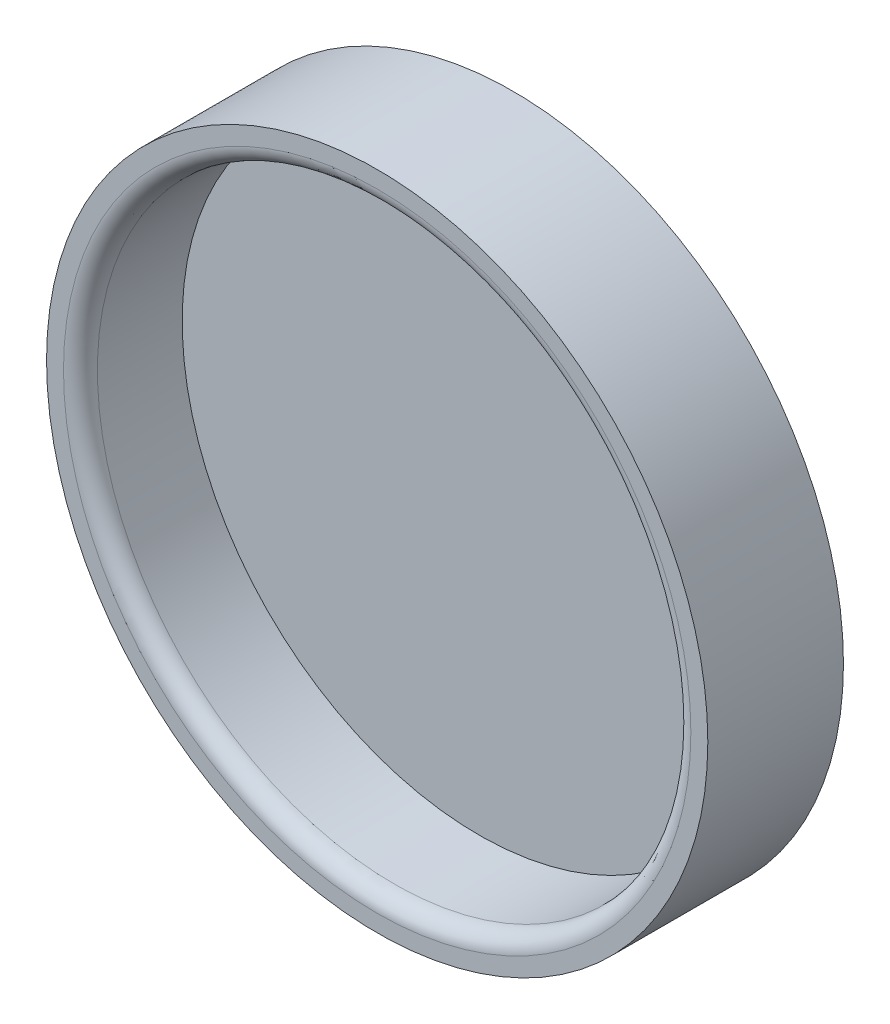
SolidWorks part; units mm, degrees
ref_plane "Front Plane" through (0, 0, 0) normal (0, 0, 1) x (1, 0, 0)
ref_plane "Top Plane" through (0, 0, 0) normal (0, 1, 0) x (1, 0, 0)
ref_plane "Right Plane" through (0, 0, 0) normal (1, 0, 0) x (0, 0, -1)
sketch "Sketch1" plane through (0, 0, 0) normal (0, 0, 1) x (1, 0, 0)
  circle A0 centre (0, 0) radius 9.75
  dimension "D1" = 19.5
extrude "Boss-Extrude1" add sketch "Sketch1" along normal blind 1
sketch "Sketch2" plane through (0, 0, 1) normal (0, 0, 1) x (1, 0, 0)
  circle A0 centre (0, 0) radius 9.75
  circle A1 centre (0, 0) radius 8.75
  circle A2 centre (0, 0) radius 9.75 construction
  dimension "D1" = 1
extrude "Boss-Extrude2" add sketch "Sketch2" along normal blind 3
fillet "Fillet1" radius 0.5 1 edges at (8.75, 0, 4)
